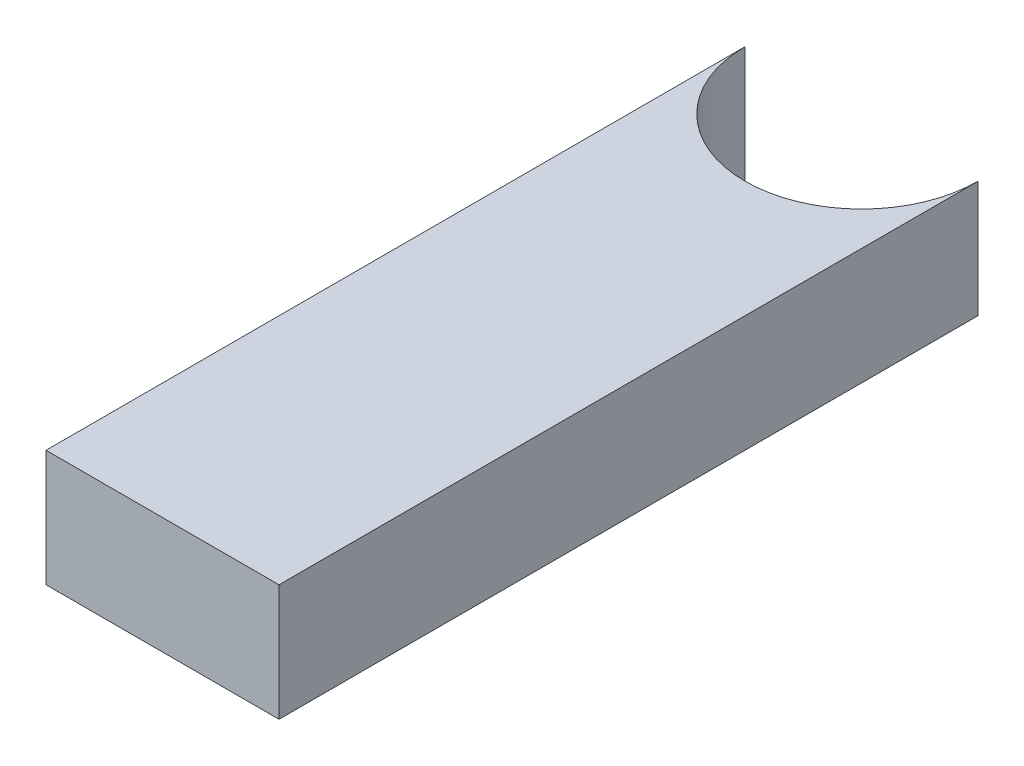
SolidWorks part; units mm, degrees
ref_plane "Front Plane" through (0, 0, 0) normal (0, 0, 1) x (1, 0, 0)
ref_plane "Top Plane" through (0, 0, 0) normal (0, 1, 0) x (1, 0, 0)
ref_plane "Right Plane" through (0, 0, 0) normal (1, 0, 0) x (0, 0, -1)
sketch "Sketch1" plane through (0, 0, 0) normal (0, 1, 0) x (1, 0, 0)
  line L0 (0, 15.24) -> (0, 0)
  line L1 (0, 0) -> (5.08, 0)
  line L2 (5.08, 0) -> (5.08, 15.24)
  arc A0 (5.08, 15.24) -> (0, 15.24) centre (2.54, 15.24) cw
  dimension "D1" = 5.08
  dimension "D2" = 15.24
extrude "Boss-Extrude1" add sketch "Sketch1" along normal blind 2.54
